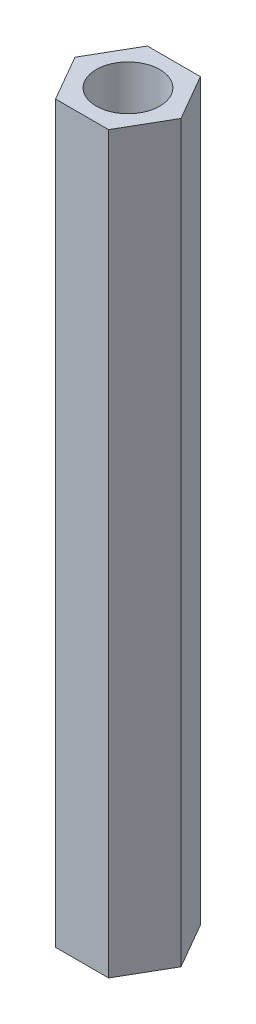
SolidWorks part; units mm, degrees
ref_plane "Front" through (0, 0, 0) normal (0, 0, 1) x (1, 0, 0)
ref_plane "Top" through (0, 0, 0) normal (0, 1, 0) x (1, 0, 0)
ref_plane "Right" through (0, 0, 0) normal (1, 0, 0) x (0, 0, -1)
sketch "Sketch1" plane through (0, 0, 0) normal (0, 1, 0) x (1, 0, 0)
  line L1 (1.8331, 3.175) -> (-1.8331, 3.175)
  line L2 (-1.8331, 3.175) -> (-3.6662, 0)
  line L3 (-3.6662, 0) -> (-1.8331, -3.175)
  line L4 (-1.8331, -3.175) -> (1.8331, -3.175)
  line L5 (1.8331, -3.175) -> (3.6662, 0)
  line L6 (3.6662, 0) -> (1.8331, 3.175)
  circle A0 centre (0, 0) radius 3.175 construction
  dimension "D1" = 6.35
extrude "Boss-Extrude1" add sketch "Sketch1" along normal blind 50.8
hole_wizard "Tap Drill for #8 Helicoil1" positions "Sketch2" profile "Sketch3" hole size "#8-32" standard "ANSI Inch"
sketch "Sketch2" plane through (0, 50.8, 0) normal (0, 1, 0) x (1, 0, 0)
  point P0 (0, 0)
sketch "Sketch3" plane through (0, 50.8, 0) normal (1, 0, 0) x (0, 0, 1)
  line L0 (0, 0) -> (0, 52.1192)
  line L1 (0, 52.1192) -> (2.1971, 50.799)
  line L2 (2.1971, 50.799) -> (2.1971, 0)
  line L5 (2.1971, 0) -> (0, 0)
  line L10 (0, 52.1192) -> (-2.1971, 50.799) construction
  line L11 (0, -6.35) -> (0, 107.95) construction
  dimension "Hole Dia." = 4.3942
  dimension "Hole Depth" = 50.799
  dimension "Drill Angle" = 118
